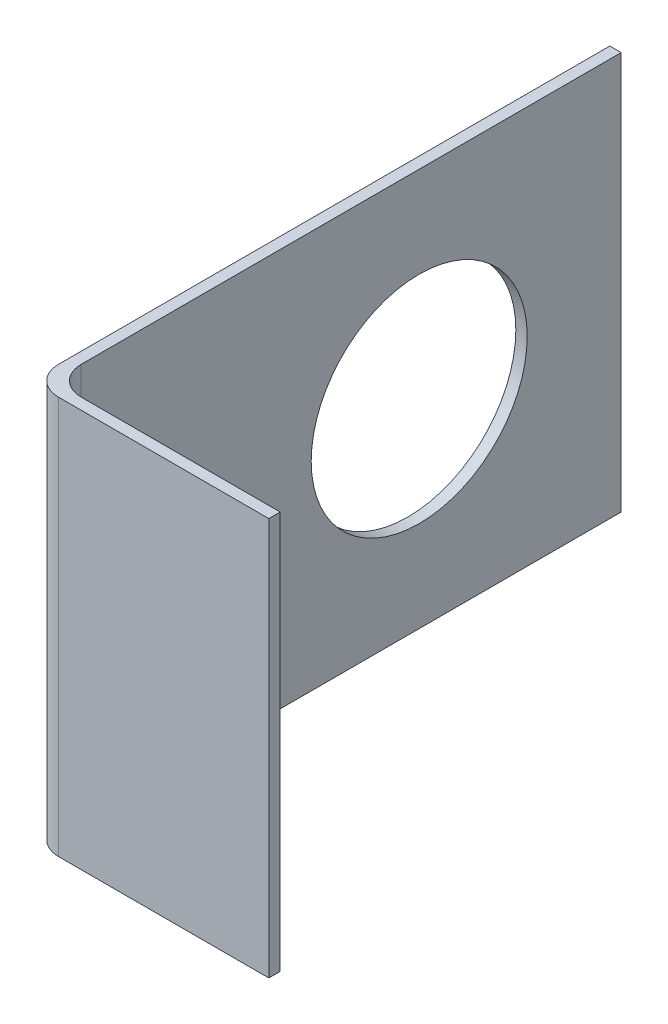
SolidWorks part; units mm, degrees
material "PPS"
ref_plane "Front Plane" through (0, 0, 0) normal (0, 0, 1) x (1, 0, 0)
ref_plane "Top Plane" through (0, 0, 0) normal (0, 1, 0) x (1, 0, 0)
ref_plane "Right Plane" through (0, 0, 0) normal (1, 0, 0) x (0, 0, -1)
sketch "Sketch1" plane through (0, 0, 0) normal (0, 1, 0) x (1, 0, 0)
  line L0 (-37.2907, 31.3561) -> (-35.2907, 31.3561)
  line L1 (-35.2907, 31.3561) -> (-35.2907, -68.6439)
  line L2 (-35.2907, -68.6439) -> (4.7093, -68.6439)
  line L3 (4.7093, -68.6439) -> (4.7093, -70.6439)
  line L4 (4.7093, -70.6439) -> (-37.2907, -70.6439)
  line L5 (-37.2907, -70.6439) -> (-37.2907, 31.3561)
  dimension "D1" = 100
  dimension "D2" = 2
  dimension "D3" = 2
  dimension "D4" = 40
extrude "Boss-Extrude1" add sketch "Sketch1" along normal blind 70
sketch "Sketch2" plane through (-37.2907, 0, 0) normal (-1, 0, 0) x (0, 0, 1)
  line L0 (70.6439, 70) -> (70.6439, 0) construction
  circle A0 centre (4.1839, 35) radius 19
  point P2 (70.6439, 35)
  dimension "D1" = 66.46
extrude "Cut-Extrude1" cut sketch "Sketch2" against normal through all
fillet "Fillet1" radius 5 2 edges at (-37.2907, 35, 70.6439) (-35.2907, 35, 68.6439)
